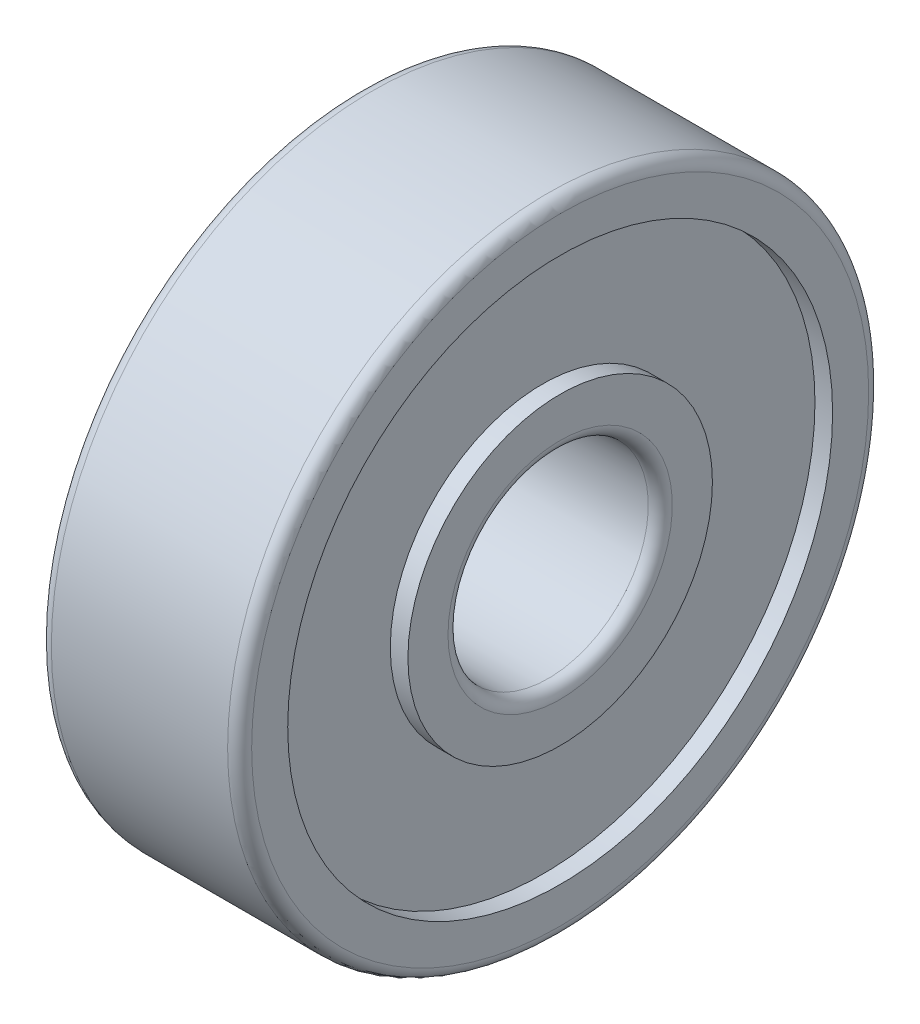
SolidWorks part; units mm, degrees
ref_plane "Front Plane" through (0, 0, 0) normal (0, 0, 1) x (1, 0, 0)
ref_plane "Top Plane" through (0, 0, 0) normal (0, 1, 0) x (1, 0, 0)
ref_plane "Right Plane" through (0, 0, 0) normal (1, 0, 0) x (0, 0, -1)
ref_plane "Plane1" through (0, 0, 0) normal (0, 0, 1) x (1, 0, 0)
sketch "Sketch1" plane through (0, 0, 0) normal (0, 0, 1) x (1, 0, 0)
  line L0 (0, 7.7) -> (0, 6.8)
  line L1 (0, 6.8) -> (0.44, 6.8)
  line L2 (0.44, 6.8) -> (0.44, 3.8)
  line L3 (0.44, 3.8) -> (0, 3.8)
  line L4 (0, 3.8) -> (0, 2.8)
  line L5 (0.3, 2.5) -> (4.7, 2.5)
  line L6 (5, 2.8) -> (5, 3.8)
  line L7 (5, 3.8) -> (4.56, 3.8)
  line L8 (4.56, 3.8) -> (4.56, 6.8)
  line L9 (4.56, 6.8) -> (5, 6.8)
  line L10 (5, 6.8) -> (5, 7.7)
  line L11 (4.7, 8) -> (0.3, 8)
  line L12 (4.7, 0) -> (0.3, 0) construction
  arc A0 (0, 2.8) -> (0.3, 2.5) centre (0.3, 2.8) ccw
  arc A1 (4.7, 2.5) -> (5, 2.8) centre (4.7, 2.8) ccw
  arc A2 (5, 7.7) -> (4.7, 8) centre (4.7, 7.7) ccw
  arc A3 (0.3, 8) -> (0, 7.7) centre (0.3, 7.7) ccw
revolve "Revolve1" add sketch "Sketch1" angle 360 about L12
